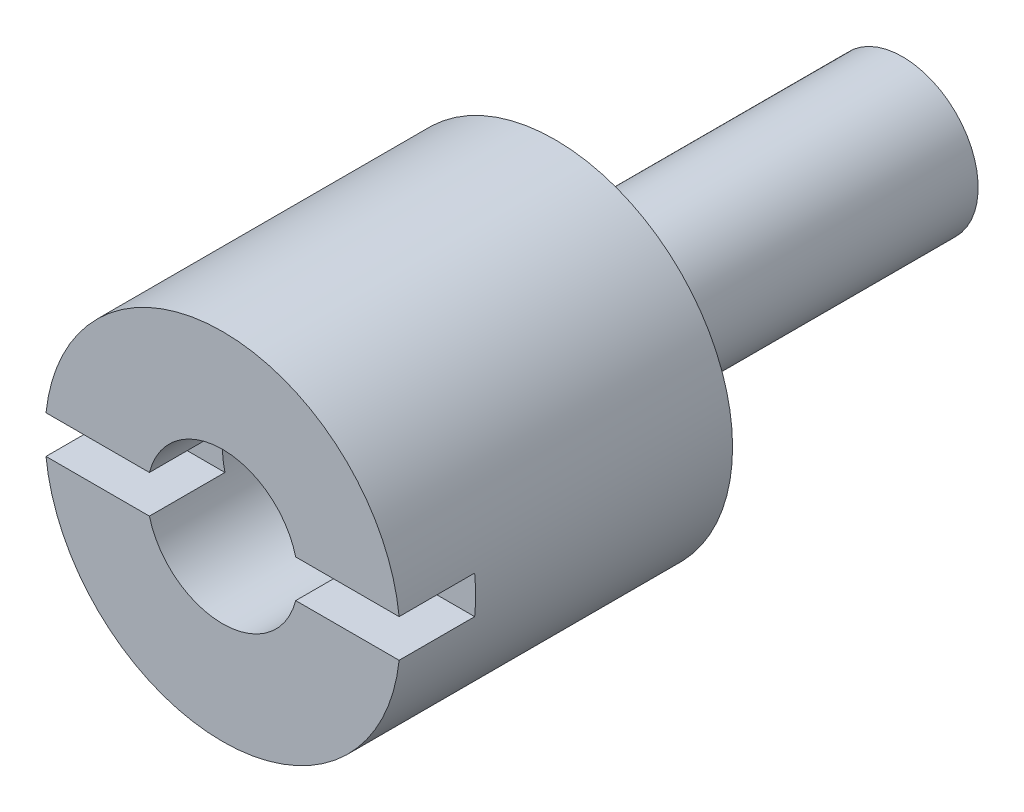
SolidWorks part; units mm, degrees
ref_plane "前视基准面" through (0, 0, 0) normal (0, 0, 1) x (1, 0, 0)
ref_plane "上视基准面" through (0, 0, 0) normal (0, 1, 0) x (1, 0, 0)
ref_plane "右视基准面" through (0, 0, 0) normal (1, 0, 0) x (0, 0, -1)
sketch "草图1" plane through (0, 0, 0) normal (0, 0, 1) x (1, 0, 0)
  circle A0 centre (0, 0) radius 2.35
  circle A1 centre (0, 0) radius 1
extrude "凸台-拉伸1" add sketch "草图1" along normal blind 4.4
sketch "草图2" plane through (0, 0, 4.4) normal (0, 0, 1) x (1, 0, 0)
  line L1 (-2.5, 0.25) -> (2.5, 0.25)
  line L2 (-2.5, 0.25) -> (-2.5, -0.25)
  line L3 (-2.5, -0.25) -> (2.5, -0.25)
  line L4 (2.5, 0.25) -> (2.5, -0.25)
  dimension "D1" = 5
  dimension "D2" = 0.5
  dimension "D3" = 0.25
  dimension "D4" = 2.5
extrude "切除-拉伸1" cut sketch "草图2" against normal blind 1
sketch "草图3" plane through (0, 0, 0) normal (0, 0, -1) x (-1, 0, 0)
  circle A0 centre (0, 0) radius 1
extrude "凸台-拉伸2" add sketch "草图3" along normal blind 4.6 separate body
